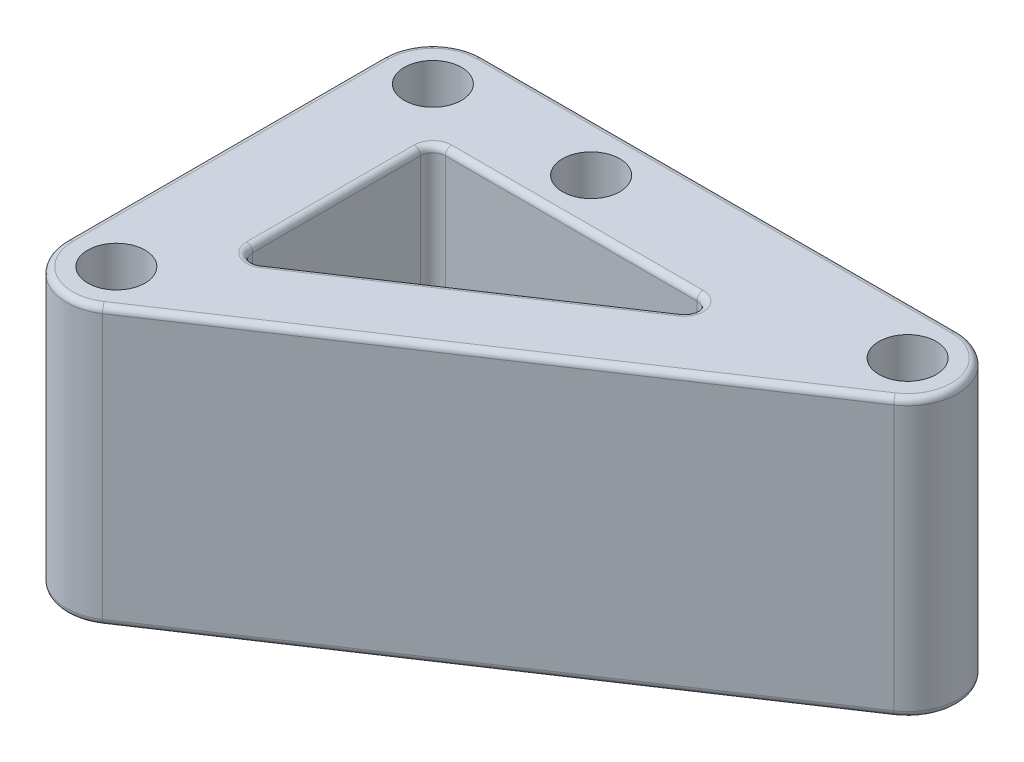
SolidWorks part; units mm, degrees
ref_plane "Front Plane" through (0, 0, 0) normal (0, 0, 1) x (1, 0, 0)
ref_plane "Top Plane" through (0, 0, 0) normal (0, 1, 0) x (1, 0, 0)
ref_plane "Right Plane" through (0, 0, 0) normal (1, 0, 0) x (0, 0, -1)
sketch "Sketch1" plane through (0, 0, 0) normal (0, 1, 0) x (1, 0, 0)
  line L0 (0, 0) -> (0, 25.4) construction
  line L1 (0, 25.4) -> (38.1, 25.4) construction
  line L3 (0, 25.4) -> (12.7, 25.4) construction
  line L4 (0, 25.4) -> (38.1, 25.4) construction
  line L6 (-4, 25.4) -> (-4, 0)
  line L7 (0, 29.4) -> (38.1, 29.4)
  line L8 (2.2188, -3.3282) -> (40.3188, 22.0718)
  line L9 (4, 21.4) -> (4, 5.0704)
  line L10 (4, 5.0704) -> (28.4944, 21.4)
  line L11 (28.4944, 21.4) -> (4, 21.4)
  circle A0 centre (0, 25.4) radius 2.3
  circle A1 centre (12.7, 25.4) radius 2.3
  circle A2 centre (38.1, 25.4) radius 2.3
  circle A3 centre (0, 0) radius 2.3
  circle A4 centre (0, 0) radius 4
  circle A5 centre (38.1, 25.4) radius 4
  circle A6 centre (0, 25.4) radius 4
  dimension "D3" = 4.6
  dimension "D9" = 8
  dimension "D1" = 25.4
  dimension "D2" = 38.1
  dimension "D5" = 12.7
  dimension "D7" = 38.1
  dimension "D10" = 6
  dimension "D11" = 8
  dimension "D12" = 8
  dimension "D4" = 2
  dimension "D6" = 2
  dimension "D8" = 2
extrude "Boss-Extrude1" add sketch "Sketch1" along normal blind 22.25 contours A6 L6 A4 L8 A5 L7 A1 L11 L10 L9 | A4 A3 | A5 A2 | A6 A0
fillet "Fillet1" radius 1 3 edges at (28.4944, 11.125, -21.4) (4, 11.125, -5.0704) (4, 11.125, -21.4)
fillet "Fillet2" radius 0.5 24 edges at (26.1488, 22.25, -20.6898) (26.1488, 0, -20.6898) (15.6505, 22.25, -12.8374) (15.6505, 0, -12.8374) (4.5281, 22.25, -6.0572) (4.5281, 0, -6.0572) (4, 22.25, -13.6694) (4, 0, -13.6694) (4.2929, 22.25, -21.1071) (4.2929, 0, -21.1071) (-1.8874, 0, 3.5267) (-1.8874, 22.25, 3.5267) (-4, 0, -12.7) (-4, 22.25, -12.7) (-2.8284, 0, -28.2284) (-2.8284, 22.25, -28.2284) (19.05, 0, -29.4) (19.05, 22.25, -29.4) (41.9284, 0, -26.5591) (41.9284, 22.25, -26.5591) (15.0958, 0, -21.4) (15.0958, 22.25, -21.4) (21.2688, 0, -9.3718) (21.2688, 22.25, -9.3718)
